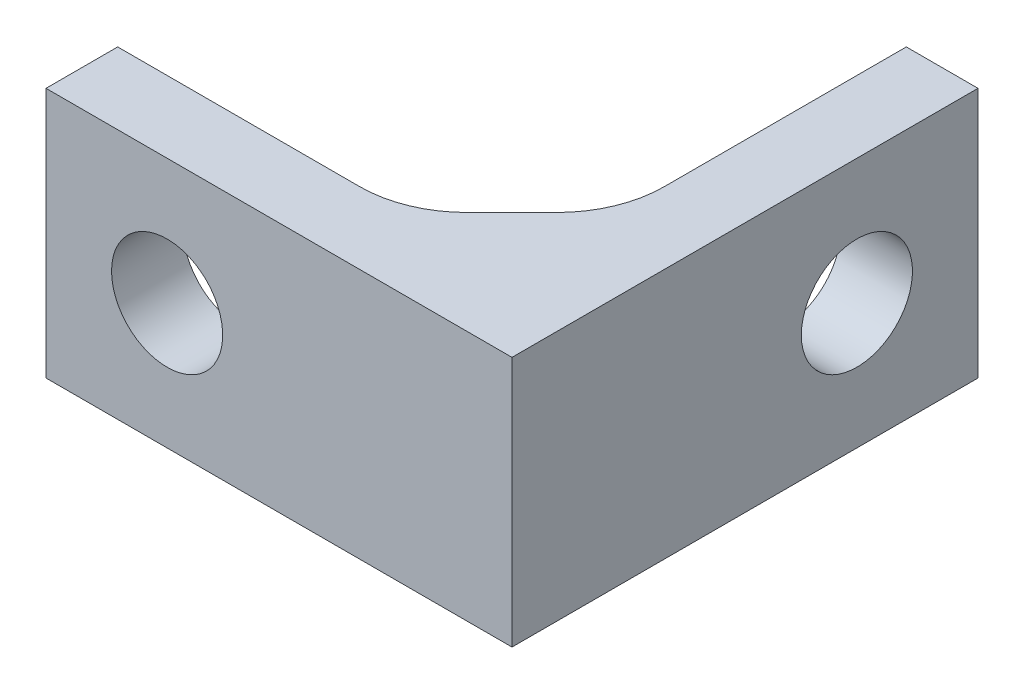
SolidWorks part; units mm, degrees
ref_plane "Спереди" through (0, 0, 0) normal (0, 0, 1) x (1, 0, 0)
ref_plane "Сверху" through (0, 0, 0) normal (0, 1, 0) x (1, 0, 0)
ref_plane "Справа" through (0, 0, 0) normal (1, 0, 0) x (0, 0, -1)
other "Configuration Table"
sketch "Sketch1" plane through (0, 0, 0) normal (0, 1, 0) x (1, 0, 0)
  line L0 (0, 0) -> (-13, 0)
  line L1 (-13, 0) -> (-13, 2)
  line L2 (-13, 2) -> (-6.2426, 2)
  line L3 (-2, 6.2426) -> (-2, 13)
  line L4 (-2, 13) -> (0, 13)
  line L5 (0, 13) -> (0, 0)
  line L6 (-2.8787, 4.1213) -> (-4.1213, 2.8787)
  arc A0 (-4.1213, 2.8787) -> (-6.2426, 2) centre (-6.2426, 5) cw
  arc A1 (-2.8787, 4.1213) -> (-2, 6.2426) centre (-5, 6.2426) ccw
  point P10 (-5, 2)
  dimension "D3" = 3
  dimension "D1" = 13
  dimension "D2" = 11
extrude "Boss-Extrude1" add sketch "Sketch1" along normal blind 7
sketch "Sketch3" plane through (0, 0, -2) normal (0, 0, -1) x (-1, 0, 0)
  line L0 (13, 3.5) -> (6.2426, 3.5) construction
  line L1 (13, 7) -> (13, 0) construction
  line L2 (6.2426, 7) -> (6.2426, 0) construction
  circle A0 centre (9.6213, 3.5) radius 1.55
  dimension "D2" = 3.1
  dimension "D1" = 6.7574
extrude "Cut-Extrude1" cut sketch "Sketch3" against normal up to next
sketch "Sketch4" plane through (-2, 0, 0) normal (-1, 0, 0) x (0, 0, 1)
  line L0 (-13, 3.5) -> (-6.2426, 3.5) construction
  line L1 (-13, 7) -> (-13, 0) construction
  line L2 (-6.2426, 7) -> (-6.2426, 0) construction
  circle A0 centre (-9.6213, 3.5) radius 1.55
  dimension "D1" = 3.1
extrude "Cut-Extrude2" cut sketch "Sketch4" against normal up to next
